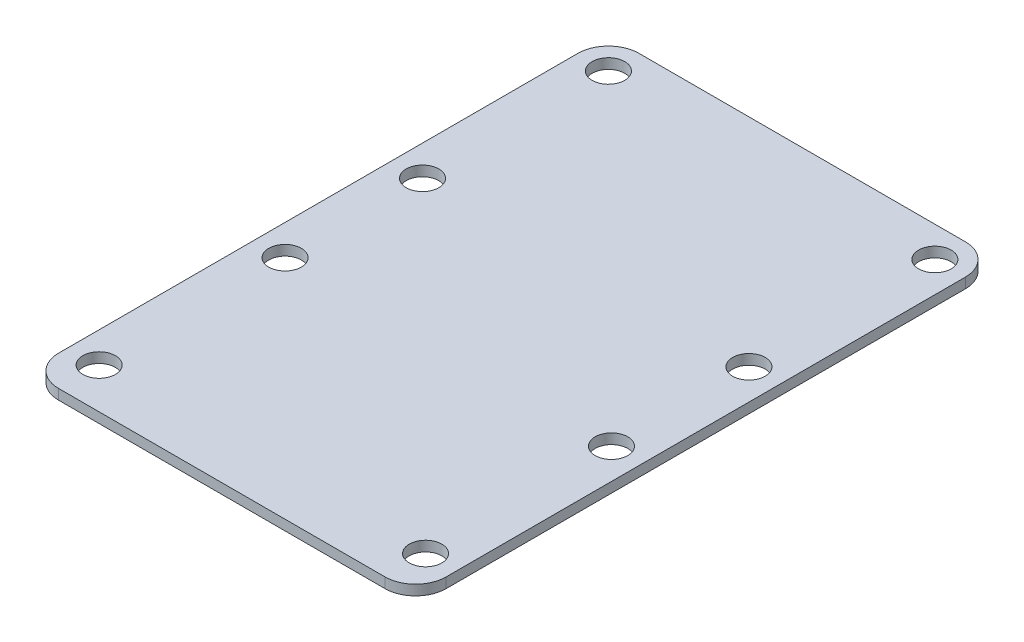
SolidWorks part; units mm, degrees
ref_plane "Front Plane" through (0, 0, 0) normal (0, 0, 1) x (1, 0, 0)
ref_plane "Top Plane" through (0, 0, 0) normal (0, 1, 0) x (1, 0, 0)
ref_plane "Right Plane" through (0, 0, 0) normal (1, 0, 0) x (0, 0, -1)
sketch "Sketch2" plane through (0, 0, 0) normal (0, 1, 0) x (1, 0, 0)
  line L0 (0, 0) -> (0, -57)
  line L1 (0, -57) -> (38.06, -57)
  line L2 (38.06, -57) -> (38.06, 0)
  line L3 (38.06, 0) -> (0, 0)
  line L4 (0, 0) -> (3, 0)
  line L5 (3, 0) -> (3, -3)
  line L6 (3, -4.53) -> (3, -19.73)
  line L7 (3, -22.79) -> (3, -33.23)
  line L8 (3, -36.29) -> (3, -51.49)
  line L9 (19.03, 0) -> (19.03, -12.0895)
  line L10 (35.06, -36.29) -> (35.06, -51.49)
  line L11 (35.06, -22.79) -> (35.06, -33.23)
  line L12 (35.06, -4.53) -> (35.06, -19.73)
  line L13 (35.06, 0) -> (35.06, -3)
  circle A0 centre (3, -3) radius 1.53
  circle A1 centre (3, -21.26) radius 1.53
  circle A2 centre (3, -34.76) radius 1.53
  circle A3 centre (3, -53.02) radius 1.53
  circle A4 centre (35.06, -53.02) radius 1.53
  circle A5 centre (35.06, -34.76) radius 1.53
  circle A6 centre (35.06, -21.26) radius 1.53
  circle A7 centre (35.06, -3) radius 1.53
  dimension "D5" = 15.2
  dimension "D6" = 3.06
  dimension "D8" = 3.06
  dimension "D9" = 3.06
  dimension "D11" = 3.06
  dimension "D1" = 57
  dimension "D2" = 38.06
  dimension "D3" = 3
  dimension "D4" = 3
  dimension "D7" = 10.44
  dimension "D10" = 15.2
extrude "Boss-Extrude1" add sketch "Sketch2" along normal blind 1
fillet "Fillet2" radius 3 4 edges at (0, 0.5, 57) (38.06, 0.5, 57) (38.06, 0.5, 0) (0, 0.5, 0)
sketch "Sketch4" plane through (0, 1, 0) normal (0, 1, 0) x (1, 0, 0)
  circle A0 centre (3, -3) radius 1.6
  circle A1 centre (3, -21.26) radius 1.6
  circle A2 centre (35.06, -3) radius 1.6
  circle A3 centre (35.06, -21.26) radius 1.6
  circle A4 centre (3, -34.76) radius 1.6
  circle A5 centre (35.06, -34.76) radius 1.6
  circle A6 centre (3, -53.02) radius 1.6
  circle A7 centre (35.06, -53.02) radius 1.6
extrude "Cut-Extrude1" cut sketch "Sketch4" against normal through all
